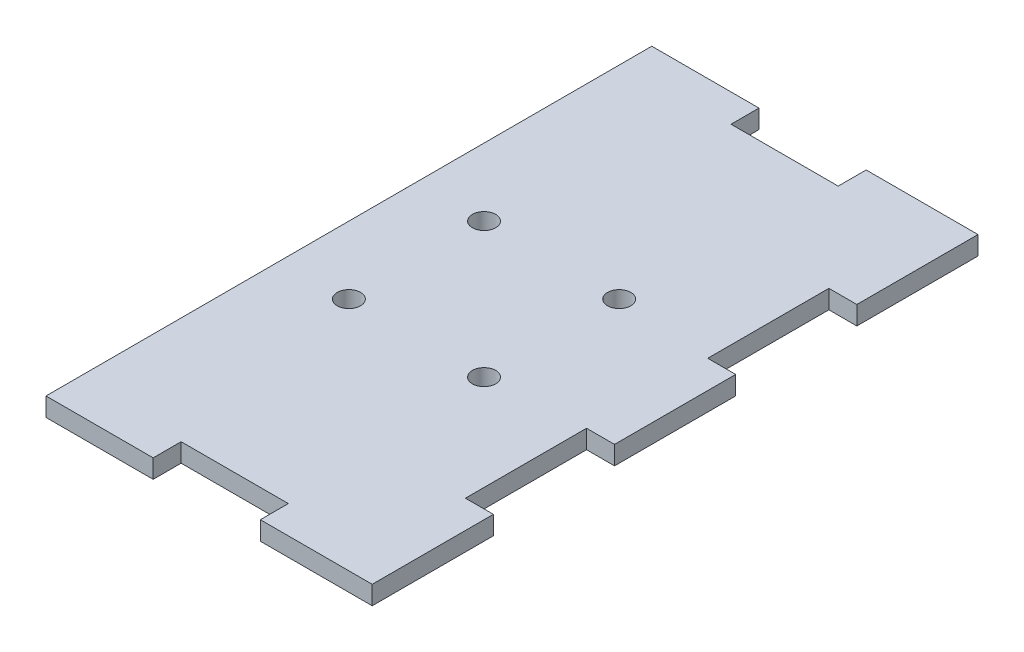
SolidWorks part; units mm, degrees
ref_plane "Front" through (0, 0, 0) normal (0, 0, 1) x (1, 0, 0)
ref_plane "Top" through (0, 0, 0) normal (0, 1, 0) x (1, 0, 0)
ref_plane "Right" through (0, 0, 0) normal (1, 0, 0) x (0, 0, -1)
sketch "Sketch1" plane through (0, 0, 0) normal (0, 1, 0) x (1, 0, 0)
  line L1 (0, 0) -> (70, 0)
  line L2 (0, 0) -> (0, 130)
  line L3 (0, 130) -> (70, 130)
  line L4 (70, 0) -> (70, 130)
  dimension "D1" = 130
  dimension "D2" = 70
extrude "Boss-Extrude1" add sketch "Sketch1" along normal blind 4
sketch "Sketch2" plane through (0, 4, 0) normal (0, 1, 0) x (1, 0, 0)
  line L0 (70, 0) -> (70, 130) construction
  line L1 (14.5, 50.5) -> (43.5, 50.5)
  line L2 (14.5, 50.5) -> (14.5, 79.5)
  line L3 (14.5, 79.5) -> (43.5, 79.5)
  line L4 (43.5, 50.5) -> (43.5, 79.5)
  line L5 (14.5, 50.5) -> (43.5, 79.5) construction
  line L6 (14.5, 79.5) -> (43.5, 50.5) construction
  line L7 (70, 130) -> (0, 130) construction
  circle A0 centre (14.5, 79.5) radius 2.5
  circle A1 centre (43.5, 79.5) radius 2.5
  circle A2 centre (43.5, 50.5) radius 2.5
  circle A3 centre (14.5, 50.5) radius 2.5
  point P0 (29, 65)
  dimension "D4" = 5
  dimension "D1" = 41
  dimension "D2" = 65
  dimension "D3" = 29
extrude "Cut-Extrude1" cut sketch "Sketch2" against normal through all contours L2 A0 L3 | L3 A0 L2 | L1 A3 L2 | L2 A3 L1 | L4 A2 L1 | L1 A2 L4 | L3 A1 L4 | L4 A1 L3
sketch "Sketch3" plane through (0, 4, 0) normal (0, 1, 0) x (1, 0, 0)
  line L0 (70, 0) -> (70, 130) construction
  line L1 (0, 0) -> (23, 0)
  line L2 (0, 0) -> (0, 6)
  line L3 (0, 6) -> (23, 6)
  line L4 (23, 0) -> (23, 6)
  line L5 (23, 0) -> (46, 0)
  line L6 (23, 0) -> (23, 6)
  line L7 (23, 6) -> (46, 6)
  line L8 (46, 0) -> (46, 6)
  line L9 (46, 0) -> (70, 0)
  line L10 (46, 0) -> (46, 6)
  line L11 (46, 6) -> (70, 6)
  line L12 (70, 0) -> (70, 6)
  line L13 (70, 130) -> (0, 130) construction
  line L14 (0, 130) -> (23, 130)
  line L15 (0, 130) -> (0, 124)
  line L16 (0, 124) -> (23, 124)
  line L17 (23, 130) -> (23, 124)
  line L18 (23, 124) -> (46, 124)
  line L19 (23, 124) -> (23, 130)
  line L20 (23, 130) -> (46, 130)
  line L21 (46, 124) -> (46, 130)
  line L23 (46, 130) -> (70, 130)
  line L24 (46, 130) -> (46, 124)
  line L25 (46, 124) -> (70, 124)
  line L26 (70, 130) -> (70, 124)
  line L27 (70, 0) -> (64, 0)
  line L28 (70, 0) -> (70, 26)
  line L29 (70, 26) -> (64, 26)
  line L30 (64, 0) -> (64, 26)
  line L31 (64, 26) -> (70, 26)
  line L32 (64, 26) -> (64, 52)
  line L33 (64, 52) -> (70, 52)
  line L34 (70, 26) -> (70, 52)
  line L35 (64, 52) -> (70, 52)
  line L36 (64, 52) -> (64, 78)
  line L37 (64, 78) -> (70, 78)
  line L38 (70, 52) -> (70, 78)
  line L39 (64, 78) -> (70, 78)
  line L40 (64, 78) -> (64, 104)
  line L41 (64, 104) -> (70, 104)
  line L42 (70, 78) -> (70, 104)
  line L43 (64, 104) -> (70, 104)
  line L44 (64, 104) -> (64, 130)
  line L45 (64, 130) -> (70, 130)
  line L46 (70, 104) -> (70, 130)
  line M27 (0, 0) -> (70, 0)
  line M28 (70, 0) -> (70, 130)
  line M29 (70, 130) -> (0, 130)
  dimension "D1" = 6
  dimension "D2" = 23
  dimension "D3" = 23
  dimension "D4" = 6
  dimension "D5" = 23
  dimension "D6" = 23
  dimension "D7" = 6
extrude "Cut-Extrude2" cut sketch "Sketch3" against normal through all contours L8 L7 L4 M27 | L33 L32 L29 M28 | L41 L40 L37 M28 | L18 L21 L17 M29
